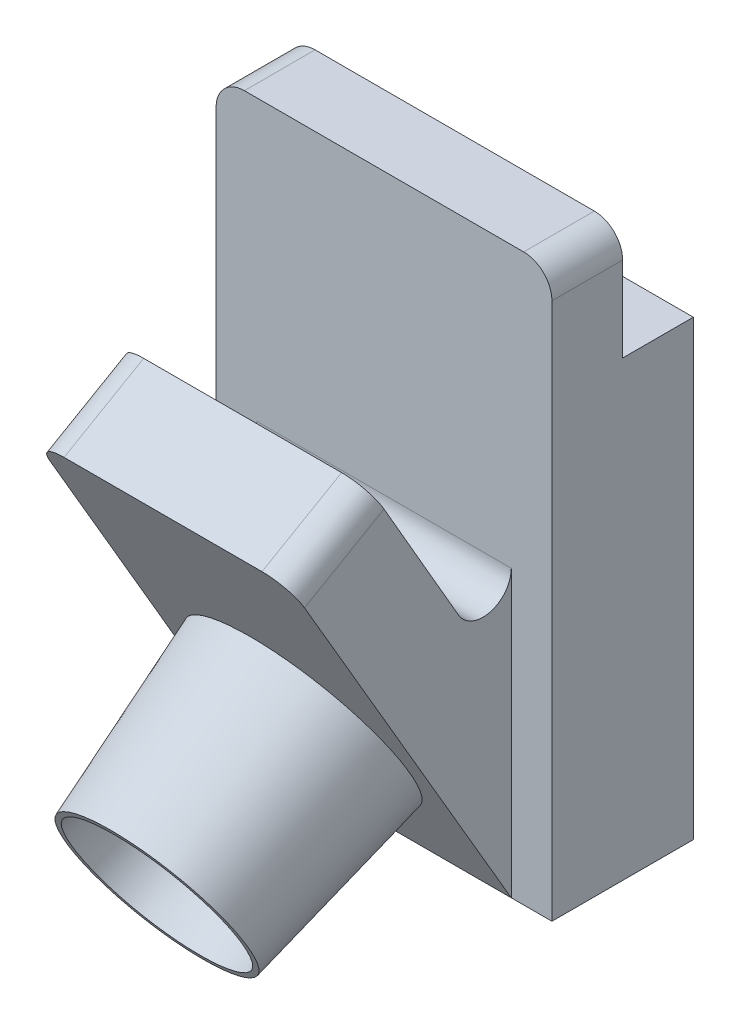
SolidWorks part; units mm, degrees
ref_plane "Front Plane" through (0, 0, 0) normal (0, 0, 1) x (1, 0, 0)
ref_plane "Top Plane" through (0, 0, 0) normal (0, 1, 0) x (1, 0, 0)
ref_plane "Right Plane" through (0, 0, 0) normal (1, 0, 0) x (0, 0, -1)
sketch "Sketch2" plane through (0, 0, 0) normal (0, 0, 1) x (1, 0, 0)
  line L1 (11.875, 16) -> (-11.875, 16)
  line L2 (11.875, 16) -> (11.875, -16)
  line L3 (11.875, -16) -> (-11.875, -16)
  line L4 (-11.875, 16) -> (-11.875, -16)
  line L5 (11.875, 16) -> (-11.875, -16) construction
  line L6 (11.875, -16) -> (-11.875, 16) construction
  point P0 (0, 0)
  dimension "D1" = 32
  dimension "D2" = 23.75
extrude "Boss-Extrude1" add sketch "Sketch2" against normal blind 5
sketch "Sketch3" plane through (0, 0, 0) normal (0, 0, 1) x (1, 0, 0)
  line L1 (-11.875, -16) -> (11.875, -16)
  line L2 (-11.875, -16) -> (-11.875, 24)
  line L3 (-11.875, 24) -> (11.875, 24)
  line L4 (11.875, -16) -> (11.875, 24)
  line L5 (0, 24) -> (0, -16) construction
  line L6 (-11.875, 4) -> (11.875, 4) construction
  point P144 (0, 4)
  dimension "D1" = 23.75
  dimension "D2" = 40
extrude "Boss-Extrude2" add sketch "Sketch3" along normal blind 5
sketch "Sketch4" plane through (11.875, 0, 0) normal (1, 0, 0) x (0, 0, -1)
  line L0 (0, 0) -> (-21.1245, 0) construction
  line L1 (0, 0) -> (-11.2003, 19.3994) construction
  line L2 (-5, -3.2778) -> (-15, 14.0427)
  line L3 (-5, -16) -> (-5, 24) construction
  line L4 (-15, 14.0427) -> (-20.6292, 10.7927)
  line L5 (-20.6292, 10.7927) -> (-5, -16)
  line L6 (-5, -16) -> (-5, -3.2778)
  dimension "D1" = 60
  dimension "D2" = 20
  dimension "D3" = 6.5
extrude "Boss-Extrude3" add sketch "Sketch4" against normal mid plane 18 from offset 11.875 offset against normal yes
sketch "Sketch5" plane through (0, -6.2384, 10.6943) normal (0, -0.5039, 0.8638) x (1, 0, 0)
  circle A0 centre (0, 0) radius 7.5
  circle A1 centre (0, 0) radius 5
  dimension "D1" = 15
  dimension "D2" = 10
extrude "Boss-Extrude4" add sketch "Sketch5" along normal blind 12 draft 5
sketch "Sketch6" plane through (0, -6.2384, 10.6943) normal (0, -0.5039, 0.8638) x (1, 0, 0)
  circle A1 centre (0, 0) radius 5
  circle A2 centre (0, 0) radius 5
  dimension "D1" = 0
extrude "Boss-Extrude5" add sketch "Sketch6" along normal blind 5 draft 45
fillet "Fillet1" radius 2 5 edges at (0, -3.2778, 5) (-11.875, 24, 2.5) (11.875, 24, 2.5) (-9, 12.4177, 17.8146) (9, 12.4177, 17.8146)
